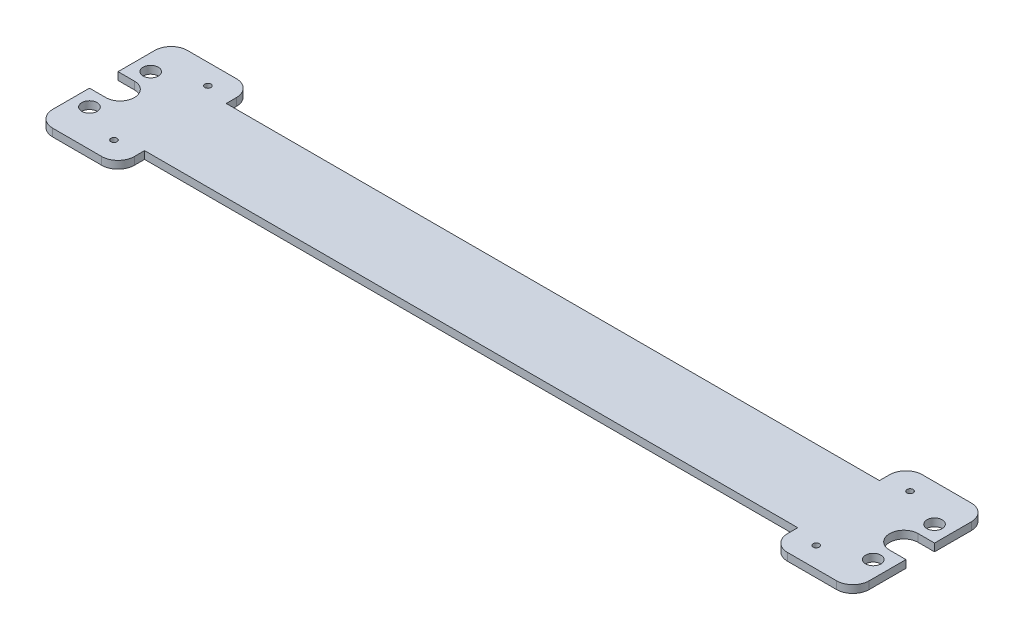
SolidWorks part; units mm, degrees
ref_plane "Front Plane" through (0, 0, 0) normal (0, 0, 1) x (1, 0, 0)
ref_plane "Top Plane" through (0, 0, 0) normal (0, 1, 0) x (1, 0, 0)
ref_plane "Right Plane" through (0, 0, 0) normal (1, 0, 0) x (0, 0, -1)
sketch "Sketch1" plane through (0, 0, 0) normal (0, 1, 0) x (1, 0, 0)
  line L0 (0, -41.91) -> (1.27, -41.91) construction
  line L1 (10.16, 0) -> (40.64, 0)
  line L2 (0, -10.16) -> (0, -33.02)
  line L3 (10.16, -83.82) -> (40.64, -83.82)
  line L4 (50.8, -10.16) -> (50.8, -16.51)
  line L5 (10.16, -50.8) -> (0, -50.8)
  line L6 (10.16, -33.02) -> (0, -33.02)
  line L7 (0, -50.8) -> (0, -73.66)
  line L8 (19.05, -41.91) -> (87.4324, -41.91) construction
  line L9 (50.8, -67.31) -> (50.8, -73.66)
  line L10 (50.8, -67.31) -> (254, -67.31)
  line L12 (50.8, -16.51) -> (254, -16.51)
  line L13 (254, -67.31) -> (254, -16.51)
  circle A0 centre (10.16, -60.96) radius 4.7625
  circle A1 centre (10.16, -22.86) radius 4.7625
  arc A2 (10.16, -50.8) -> (10.16, -33.02) centre (10.16, -41.91) ccw
  circle A3 centre (10.16, -22.86) radius 6.35 construction
  circle A4 centre (10.16, -60.96) radius 6.35 construction
  arc A5 (0, -73.66) -> (10.16, -83.82) centre (10.16, -73.66) ccw
  arc A6 (10.16, 0) -> (0, -10.16) centre (10.16, -10.16) ccw
  circle A7 centre (35.56, -71.12) radius 1.905
  circle A8 centre (35.56, -12.7) radius 1.905
  arc A9 (40.64, -83.82) -> (50.8, -73.66) centre (40.64, -73.66) ccw
  arc A10 (40.64, 0) -> (50.8, -10.16) centre (40.64, -10.16) cw
  point P22 (0, -83.82)
  point P25 (0, 0)
  point P35 (0, 0)
  point P38 (50.8, -83.82)
  dimension "D3" = 9.525
  dimension "D4" = 9.525
  dimension "D5" = 17.78
  dimension "D10" = 41.91
  dimension "D11" = 12.7
  dimension "D12" = 12.7
  dimension "D13" = 10.16
  dimension "D14" = 3.81
  dimension "D15" = 3.81
  dimension "D22" = 10.16
  dimension "D1" = 83.82
  dimension "D2" = 50.8
  dimension "D6" = 19.05
  dimension "D7" = 19.05
  dimension "D8" = 10.16
  dimension "D9" = 10.16
  dimension "D16" = 12.7
  dimension "D17" = 12.7
  dimension "D18" = 203.2
  dimension "D19" = 50.8
  dimension "D20" = 16.51
  dimension "D21" = 15.24
extrude "Boss-Extrude1" add sketch "Sketch1" along normal blind 4.7625
mirror "Mirror1" about plane through (254, 4.7625, 67.31) normal (-1, 0, 0) of "Boss-Extrude1"
